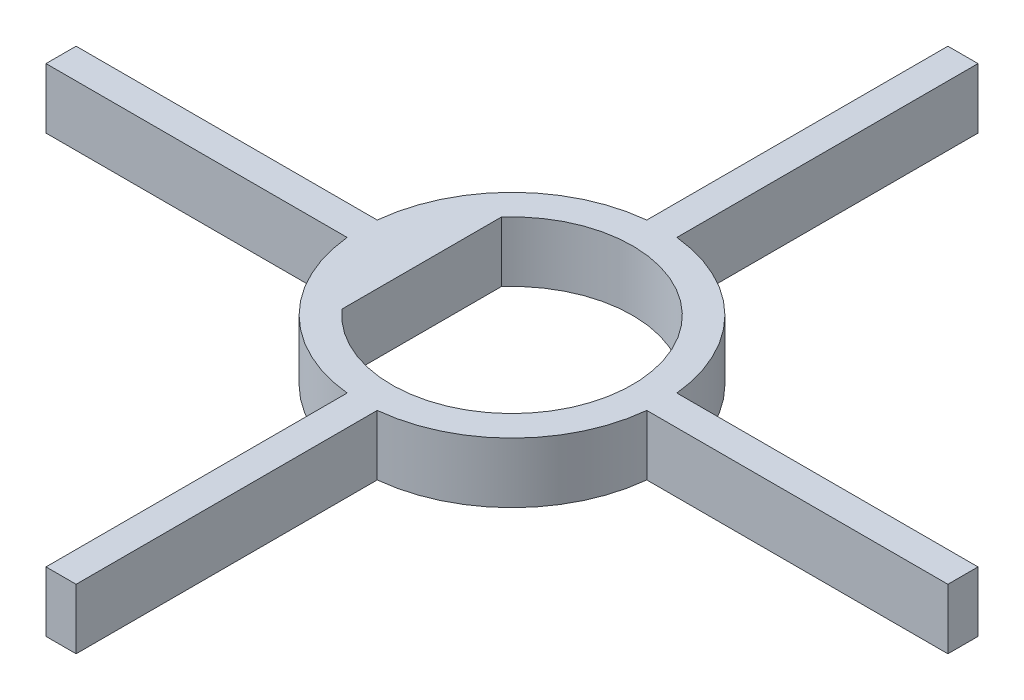
SolidWorks part; units mm, degrees
ref_plane "Front Plane" through (0, 0, 0) normal (0, 0, 1) x (1, 0, 0)
ref_plane "Top Plane" through (0, 0, 0) normal (0, 1, 0) x (1, 0, 0)
ref_plane "Right Plane" through (0, 0, 0) normal (1, 0, 0) x (0, 0, -1)
sketch "Sketch1" plane through (0, 0, 0) normal (0, 1, 0) x (1, 0, 0)
  line L0 (-0.5, 4.9749) -> (-0.5, 14.9749)
  line L1 (-0.5, 14.9749) -> (0.5, 14.9749)
  line L2 (0.5, 14.9749) -> (0.5, 4.9749)
  line L3 (4.9749, 0.5) -> (14.9749, 0.5)
  line L4 (14.9749, 0.5) -> (14.9749, -0.5)
  line L5 (14.9749, -0.5) -> (4.9749, -0.5)
  line L6 (0.5, -4.9749) -> (0.5, -14.9749)
  line L7 (0.5, -14.9749) -> (-0.5, -14.9749)
  line L8 (-0.5, -14.9749) -> (-0.5, -4.9749)
  line L9 (-4.9749, -0.5) -> (-14.9749, -0.5)
  line L10 (-14.9749, -0.5) -> (-14.9749, 0.5)
  line L11 (-14.9749, 0.5) -> (-4.9749, 0.5)
  arc A0 (-4.9749, -0.5) -> (-0.5, -4.9749) centre (0, 0) ccw
  arc A1 (-0.5, 4.9749) -> (-4.9749, 0.5) centre (0, 0) ccw
  arc A2 (4.9749, 0.5) -> (0.5, 4.9749) centre (0, 0) ccw
  arc A3 (0.5, -4.9749) -> (4.9749, -0.5) centre (0, 0) ccw
  point P8 (0, -14.9749)
  point P9 (-14.9749, 0)
  point P10 (14.9749, 0)
  point P23 (-24.5368, -4.3704)
  dimension "D1" = 10
  dimension "D2" = 1
  dimension "D3" = 10
  dimension "D4" = 4
extrude "Boss-Extrude1" add sketch "Sketch1" along normal blind 2
sketch "Sketch2" plane through (0, 0, 0) normal (0, 1, 0) x (1, 0, 0)
  line L4 (-3, -2.6458) -> (-3, 2.6458)
  arc A0 (-3, -2.6458) -> (-3, 2.6458) centre (0, 0) ccw
  point P3 (-7.0218, 0)
  dimension "D1" = 8
  dimension "D2" = 3
extrude "Cut-Extrude1" cut sketch "Sketch2" against normal through all and the other way through all contours A0 L4
